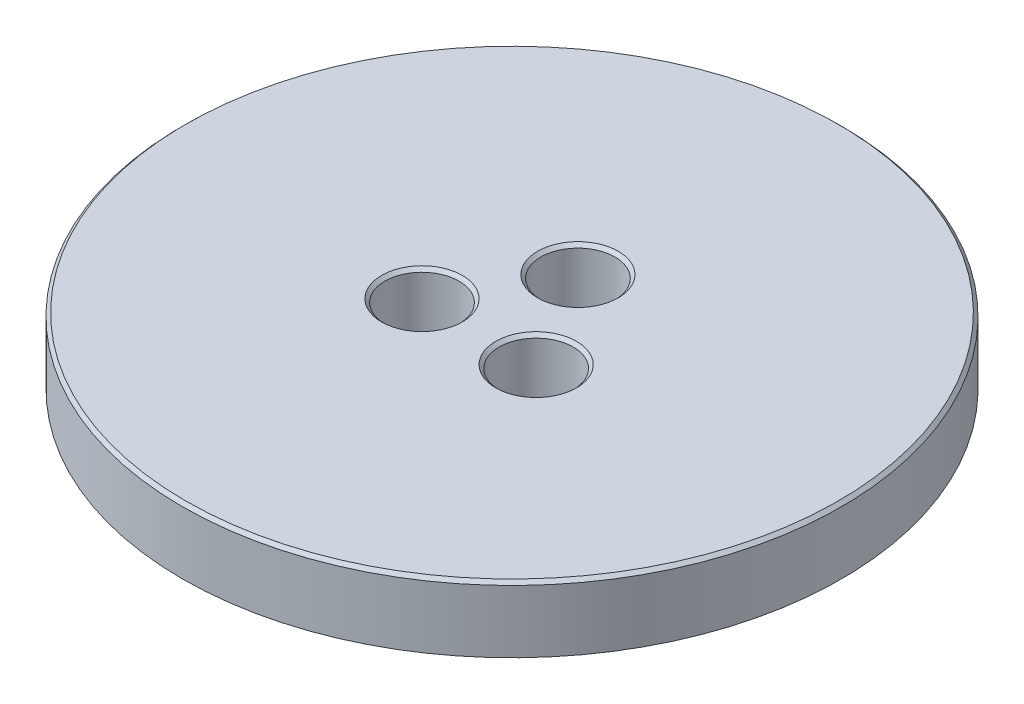
SolidWorks part; units mm, degrees
ref_plane "Front Plane" through (0, 0, 0) normal (0, 0, 1) x (1, 0, 0)
ref_plane "Top Plane" through (0, 0, 0) normal (0, 1, 0) x (1, 0, 0)
ref_plane "Right Plane" through (0, 0, 0) normal (1, 0, 0) x (0, 0, -1)
sketch "Sketch1" plane through (0, 0, 0) normal (0, 0, 1) x (1, 0, 0)
  line L12 (0, 0) -> (10, 0)
  line L13 (0, 0) -> (0, 2)
  line L15 (10, 0) -> (10, 2)
  line L16 (0, 2) -> (10, 2)
  dimension "D1" = 10
  dimension "D2" = 2
revolve "Revolve1" add sketch "Sketch1" angle 360 about L13
sketch "Sketch2" plane through (0, 0, 0) normal (0, 1, 0) x (1, 0, 0)
  line L0 (5.2984, 6.7299) -> (4.467, -0.1852) construction
  line L2 (0, 0) -> (-4.8092, -7.6356) construction
  line L4 (0, 0) -> (4.8092, -7.6356) construction
  line L6 (5.1427, 5.4349) -> (4.7787, 2.4076) construction
  line L7 (5.1427, 5.4349) -> (8.1701, 5.0709) construction
  line L8 (4.7787, 2.4076) -> (7.8061, 2.0436) construction
  line L9 (8.1701, 5.0709) -> (7.8061, 2.0436) construction
  line L10 (4.9152, 3.5428) -> (7.9426, 3.1788) construction
  line L12 (6.2924, 2.2256) -> (6.6564, 5.2529) construction
  line L14 (6.4289, 3.3608) -> (6.5935, 4.73)
  line L15 (6.4289, 3.3608) -> (7.9426, 3.1788) construction
  line L16 (6.4289, 3.3608) -> (6.6116, 4.8802) construction
  line L17 (7.9426, 3.1788) -> (8.1253, 4.6982) construction
  line L18 (6.6116, 4.8802) -> (8.1253, 4.6982) construction
  line L19 (6.4289, 3.3608) -> (8.1253, 4.6982) construction
  line L20 (7.9426, 3.1788) -> (6.6116, 4.8802) construction
  line L21 (6.7048, 4.7611) -> (7.2384, 4.0789)
  line L22 (7.3263, 4.0684) -> (8.0064, 4.6046)
  line L23 (8.1072, 4.548) -> (7.9426, 3.1788)
  line L24 (-1.7321, -1) -> (0, 0) construction
  line L25 (0, 0) -> (1.7321, -1) construction
  line L26 (0, 2) -> (0, 0) construction
  circle A5 centre (0, 0) radius 9.625 construction
  circle A6 centre (0, 5.158) radius 4.467
  circle A7 centre (4.467, -2.579) radius 4.467
  circle A8 centre (-4.467, -2.579) radius 4.467
  circle A9 centre (-6.4683, 3.7345) radius 2.1561
  circle A10 centre (6.4683, 3.7345) radius 2.1561
  circle A11 centre (0, -7.4689) radius 2.1561
  circle A12 centre (-3.179, -7.9535) radius 1.0597
  circle A13 centre (3.179, -7.9535) radius 1.0597
  circle A14 centre (8.4775, 1.2236) radius 1.0597
  circle A15 centre (5.2984, 6.7299) radius 1.0597
  circle A16 centre (-8.4775, 1.2236) radius 1.0597
  circle A17 centre (-5.2984, 6.7299) radius 1.0597
  circle A18 centre (0, 0) radius 0.691
  circle A19 centre (-4.1516, 2.3969) radius 0.519
  circle A20 centre (0, -4.7939) radius 0.519
  circle A21 centre (4.1516, 2.3969) radius 0.519
  circle A22 centre (-9.0172, -0.3471) radius 0.6011
  circle A23 centre (-4.208, 7.9826) radius 0.6011
  circle A24 centre (4.208, 7.9826) radius 0.6011
  circle A25 centre (9.0172, -0.3471) radius 0.6011
  circle A26 centre (4.8092, -7.6356) radius 0.6011
  circle A27 centre (-4.8092, -7.6356) radius 0.6011
  circle A32 centre (-4.467, -0.1852) radius 2.0731 construction
  circle A33 centre (-6.5401, -3.7759) radius 2.0731 construction
  circle A34 centre (-2.3938, -3.7759) radius 2.0731 construction
  circle A35 centre (-1.7321, -1) radius 1.125
  circle A36 centre (0, 7.5519) radius 2.0731 construction
  circle A37 centre (2.0731, 3.9611) radius 2.0731 construction
  circle A38 centre (-2.0731, 3.9611) radius 2.0731 construction
  circle A39 centre (4.467, -0.1852) radius 2.0731 construction
  circle A40 centre (6.5401, -3.7759) radius 2.0731 construction
  circle A41 centre (2.3938, -3.7759) radius 2.0731 construction
  circle A42 centre (1.7321, -1) radius 1.125
  circle A43 centre (0, 2) radius 1.125
  circle A50 centre (-5.7181, -7.263) radius 0.3812
  circle A51 centre (-9.149, -1.3205) radius 0.3812
  circle A52 centre (-3.4309, 8.5835) radius 0.3812
  circle A53 centre (3.4309, 8.5835) radius 0.3812
  circle A54 centre (9.149, -1.3205) radius 0.3812
  circle A55 centre (5.7181, -7.263) radius 0.3812
  circle A129 centre (0.8413, 0.4857) radius 0.2804
  circle A130 centre (-6.7134, 6.2984) radius 0.4196
  circle A131 centre (-8.8113, 2.6647) radius 0.4196
  circle A132 centre (-7.1289, 1.372) radius 0.297
  circle A133 centre (-4.7526, 5.4878) radius 0.297
  circle A134 centre (-2.0979, -8.9632) radius 0.4196
  circle A135 centre (2.0979, -8.9632) radius 0.4196
  circle A136 centre (2.3763, -6.8598) radius 0.297
  circle A137 centre (-2.3763, -6.8598) radius 0.297
  circle A138 centre (8.8113, 2.6647) radius 0.4196
  circle A139 centre (7.1289, 1.372) radius 0.297
  circle A140 centre (4.7526, 5.4878) radius 0.297
  circle A141 centre (6.7134, 6.2984) radius 0.4196
  circle A142 centre (-9.1553, -1.9633) radius 0.2616
  circle A143 centre (-2.8774, 8.9104) radius 0.2616
  circle A144 centre (2.8774, 8.9104) radius 0.2616
  circle A145 centre (9.1553, -1.9633) radius 0.2616
  circle A146 centre (6.2779, -6.9471) radius 0.2616
  circle A147 centre (-6.2779, -6.9471) radius 0.2616
  circle A148 centre (-0.8413, 0.4857) radius 0.2804
  circle A149 centre (0, -0.9715) radius 0.2804
  circle A150 centre (-4.1955, 3.1143) radius 0.1998
  circle A151 centre (-3.5001, 2.0208) radius 0.2333
  circle A152 centre (-4.7948, 2.0762) radius 0.1998
  circle A153 centre (-8.8052, 3.3044) radius 0.2201
  circle A154 centre (-9.1937, 2.2197) radius 0.1672
  circle A155 centre (-8.3274, 2.4039) radius 0.1301
  circle A156 centre (-9.4089, 0.3622) radius 0.2091
  circle A157 centre (-8.3247, 0) radius 0.1734
  circle A158 centre (-7.2643, 5.9734) radius 0.2201
  circle A159 centre (-6.5192, 6.8521) radius 0.1672
  circle A160 centre (-6.2456, 6.0098) radius 0.1301
  circle A161 centre (-5.0181, 7.9673) radius 0.2091
  circle A162 centre (-4.1624, 7.2094) radius 0.1734
  circle A163 centre (-2.4703, 9.1059) radius 0.19
  circle A164 centre (-9.121, -2.4136) radius 0.19
  circle A165 centre (2.4703, 9.1059) radius 0.19
  circle A166 centre (5.0181, 7.9673) radius 0.2091
  circle A167 centre (4.1624, 7.2094) radius 0.1734
  circle A168 centre (7.2643, 5.9734) radius 0.2201
  circle A169 centre (6.5192, 6.8521) radius 0.1672
  circle A170 centre (6.2456, 6.0098) radius 0.1301
  circle A171 centre (4.1955, 3.1143) radius 0.1998
  circle A172 centre (4.7948, 2.0762) radius 0.1998
  circle A173 centre (3.5001, 2.0208) radius 0.2333
  circle A174 centre (8.8052, 3.3044) radius 0.2201
  circle A175 centre (9.1937, 2.2197) radius 0.1672
  circle A176 centre (9.4089, 0.3622) radius 0.2091
  circle A177 centre (8.3247, 0) radius 0.1734
  circle A178 centre (9.121, -2.4136) radius 0.19
  circle A179 centre (0, -4.0416) radius 0.2333
  circle A180 centre (0.5994, -5.1906) radius 0.1998
  circle A181 centre (-0.5994, -5.1906) radius 0.1998
  circle A182 centre (-6.6508, -6.6923) radius 0.19
  circle A183 centre (6.6508, -6.6923) radius 0.19
  circle A184 centre (1.5409, -9.2778) radius 0.2201
  circle A185 centre (2.6745, -9.0718) radius 0.1672
  circle A186 centre (-1.5409, -9.2778) radius 0.2201
  circle A187 centre (-2.6745, -9.0718) radius 0.1672
  circle A188 centre (-4.3908, -8.3295) radius 0.2091
  circle A189 centre (4.3908, -8.3295) radius 0.2091
  circle A190 centre (4.1624, -7.2094) radius 0.1734
  circle A191 centre (-4.1624, -7.2094) radius 0.1734
  arc A192 (4.9152, 3.5428) -> (6.4289, 3.3608) centre (5.6721, 3.4518) ccw
  arc A193 (8.0064, 4.6046) -> (8.1072, 4.548) centre (8.0451, 4.5555) cw
  arc A194 (7.2384, 4.0789) -> (7.3263, 4.0684) centre (7.2876, 4.1175) ccw
  arc A195 (6.7048, 4.7611) -> (6.5935, 4.73) centre (6.6556, 4.7226) ccw
  point P0 (0, 0)
  point P189 (7.2771, 4.0295)
  point P193 (7.2771, 4.0295)
  point P196 (6.6116, 4.8802)
  dimension "D4" = 1.5246
  dimension "D6" = 0.0625
  dimension "D1" = 19.25
  dimension "D7" = 2.25
  dimension "D8" = 2.25
  dimension "D9" = 2.25
  dimension "D2" = 3.0492
  dimension "D3" = 1.9058
  dimension "D5" = 1.5304
  dimension "D10" = 120
  dimension "D11" = 120
  dimension "D12" = 2
  dimension "D13" = 2
  dimension "D14" = 2
extrude "Cut-Extrude1" cut sketch "Sketch2" along normal through all contours A43 | A35 | A42
chamfer "Chamfer2" distance 0.1 angle 45 4 edges at (0, 2, -10) (1.7321, 2, 2.125) (-1.7321, 2, 2.125) (0, 2, -0.875)
equation "\"D\"= \"B\" - 0.75'design diameter"
equation "\"B\"= 20mm'button diameter"
equation "\"h\"= 0.099 * \"D\"'offset of JM from of box"
equation "\"w\"= 0.0795 * \"D\"'width of J"
equation "\"D1@Sketch2\"= \"D\""
equation "\"D3@Sketch2\"=\"h\""
equation "\"D5@Sketch2\"=\"w\""
equation "\"D1@Sketch1\"=\"B\"/2"
